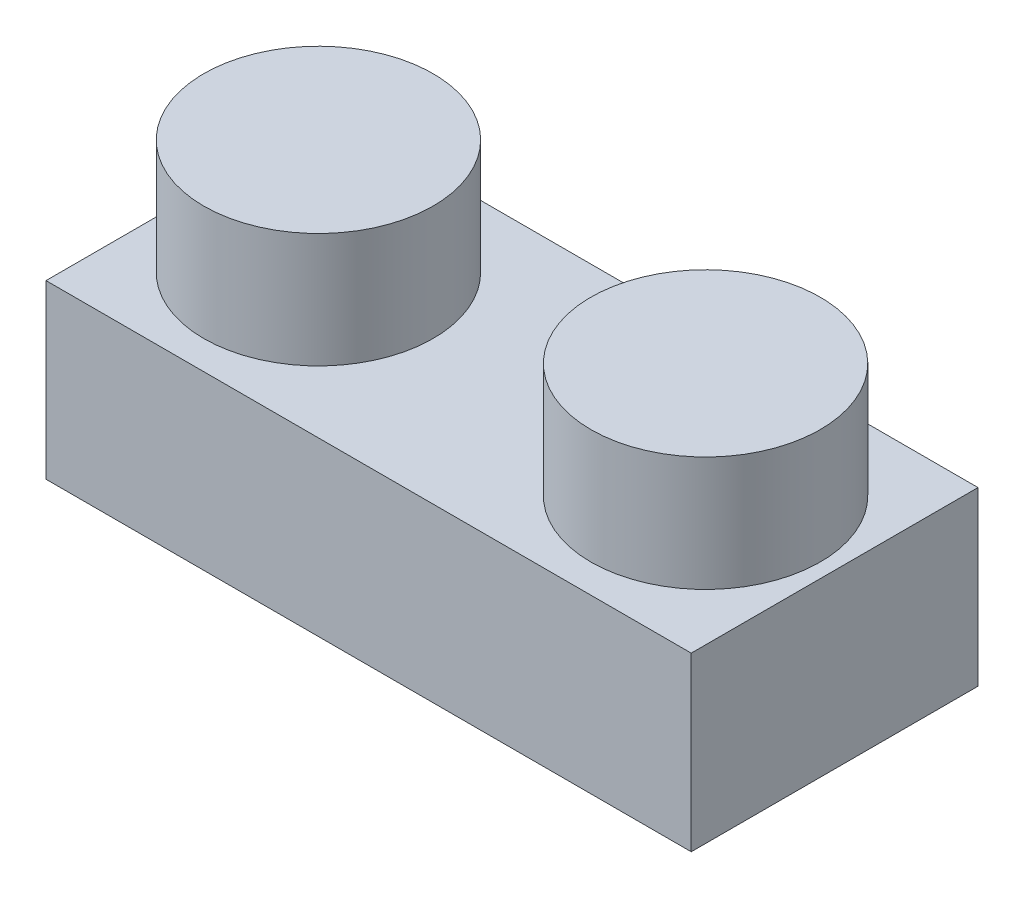
SolidWorks part; units mm, degrees
material "ABS PC"
ref_plane "Front Plane" through (0, 0, 0) normal (0, 0, 1) x (1, 0, 0)
ref_plane "Top Plane" through (0, 0, 0) normal (0, 1, 0) x (1, 0, 0)
ref_plane "Right Plane" through (0, 0, 0) normal (1, 0, 0) x (0, 0, -1)
sketch "Sketch1" plane through (0, 0, 0) normal (0, 1, 0) x (1, 0, 0)
  line L1 (-22.5, 10) -> (22.5, 10)
  line L2 (-22.5, 10) -> (-22.5, -10)
  line L3 (-22.5, -10) -> (22.5, -10)
  line L4 (22.5, 10) -> (22.5, -10)
  line L5 (-22.5, 10) -> (22.5, -10) construction
  line L6 (-22.5, -10) -> (22.5, 10) construction
  point P0 (0, 0)
  dimension "D1" = 45
  dimension "D2" = 20
extrude "Boss-Extrude1" add sketch "Sketch1" along normal blind 12
sketch "Sketch2" plane through (0, 12, 0) normal (0, 1, 0) x (1, 0, 0)
  line L0 (-6.6, 0) -> (6.6, 0) construction
  line L1 (0, -6.6) -> (0, 6.6) construction
  circle A0 centre (-13.5, 0) radius 8
  circle A1 centre (13.5, 0) radius 8
  dimension "D1" = 27
  dimension "D2" = 16
  dimension "D3" = 13.5
extrude "Boss-Extrude2" add sketch "Sketch2" along normal blind 8
